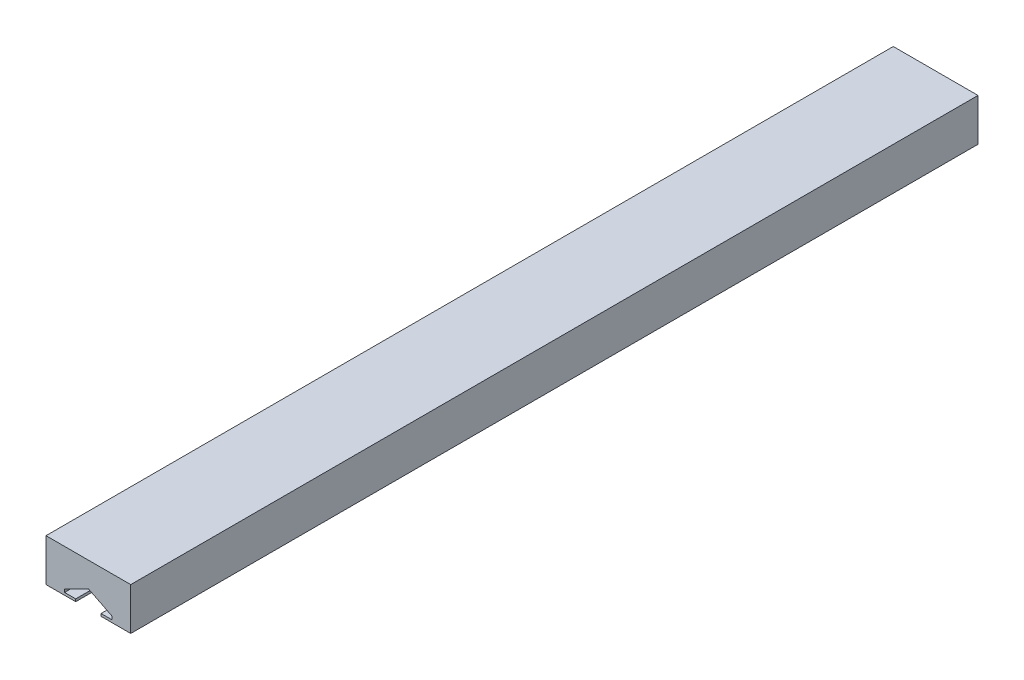
SolidWorks part; units mm, degrees
ref_plane "前视基准面" through (0, 0, 0) normal (0, 0, 1) x (1, 0, 0)
ref_plane "上视基准面" through (0, 0, 0) normal (0, 1, 0) x (1, 0, 0)
ref_plane "右视基准面" through (0, 0, 0) normal (1, 0, 0) x (0, 0, -1)
sketch "草图1" plane through (0, 0, 0) normal (0, 0, 1) x (1, 0, 0)
  line L0 (0, 5) -> (0, -5) construction
  line L1 (10, -5) -> (2.9912, -5)
  line L2 (10, -5) -> (10, 5)
  line L3 (10, 5) -> (-10, 5)
  line L4 (-10, -5) -> (-10, 5)
  line L5 (10, -5) -> (-10, 5) construction
  line L6 (10, 5) -> (-10, -5) construction
  line L7 (-2.9912, -5) -> (-2.9912, -4.4151)
  line L8 (-2.9912, -4.4151) -> (-5.6161, -4.4151)
  line L9 (-5.6161, -4.4151) -> (-5.6161, -3.6668)
  line L10 (-5.6161, -3.6668) -> (0, -0.8588)
  line L11 (5.6161, -3.6668) -> (0, -0.8588)
  line L12 (5.6161, -4.4151) -> (5.6161, -3.6668)
  line L13 (2.9912, -5) -> (2.9912, -4.4151)
  line L14 (2.9912, -4.4151) -> (5.6161, -4.4151)
  line L15 (-2.9912, -5) -> (-10, -5)
  point P0 (0, 0)
  dimension "D1" = 10
  dimension "D2" = 20
extrude "凸台-拉伸1" add sketch "草图1" along normal blind 200
